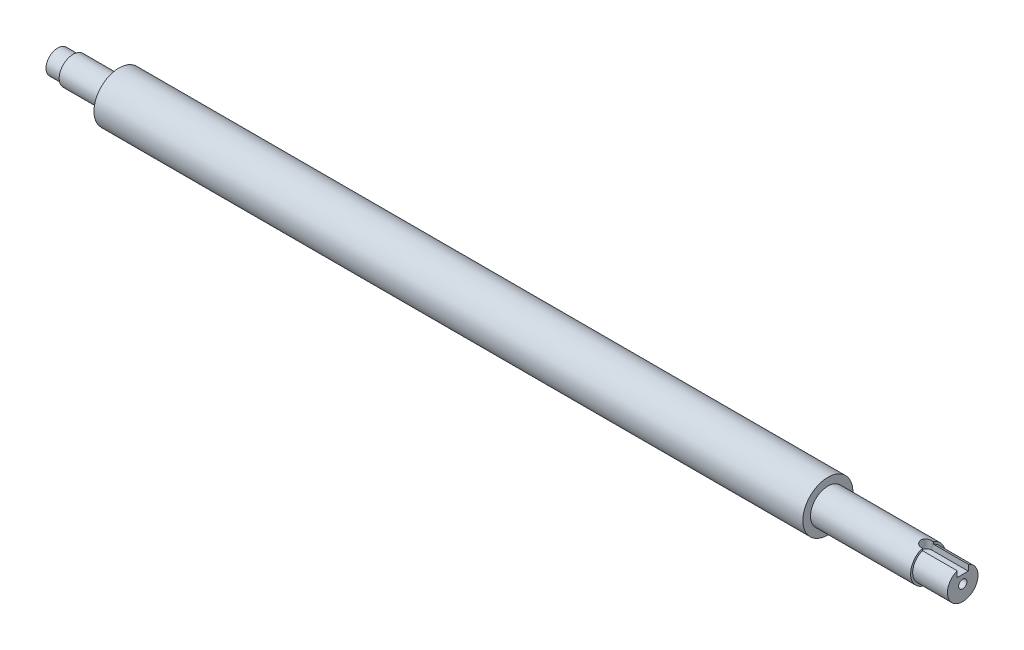
SolidWorks part; units mm, degrees
ref_plane "Front Plane" through (0, 0, 0) normal (0, 0, 1) x (1, 0, 0)
ref_plane "Top Plane" through (0, 0, 0) normal (0, 1, 0) x (1, 0, 0)
ref_plane "Right Plane" through (0, 0, 0) normal (1, 0, 0) x (0, 0, -1)
sketch "Sketch1" plane through (0, 0, 0) normal (0, 0, 1) x (1, 0, 0)
  line L0 (254.2407, 11) -> (279.2407, 11)
  line L1 (279.2407, 11) -> (279.2407, 0)
  line L2 (-360.7593, 8.5) -> (-371.7593, 8.5)
  line L3 (279.2407, 0) -> (-371.7593, 0)
  line L4 (-360.7593, 10) -> (-360.7593, 8.5)
  line L5 (182.2407, 18) -> (-327.7593, 18)
  line L6 (254.2407, 50.6061) -> (254.2407, -26.5676) construction
  line L7 (-327.7593, 10) -> (-360.7593, 10)
  line L8 (-361.2229, 15) -> (-361.2229, -3.8009) construction
  line L9 (-327.7593, 18) -> (-327.7593, 10)
  line L10 (-361.2229, 20) -> (-361.2229, -20) construction
  line L11 (-361.2229, 9.1) -> (-361.2229, -9.1) construction
  line L12 (-371.7593, 8.5) -> (-371.7593, 0)
  line L13 (-333.7229, -65.1183) -> (-333.7229, 170) construction
  line L14 (182.2407, 18) -> (182.2407, 12.5)
  line L17 (182.2407, 12.5) -> (254.2407, 12.5)
  line L18 (254.2407, 12.5) -> (254.2407, 11)
  point P10 (-44.4306, 234.5066)
  point P11 (-369.5152, 234.5066)
  point P14 (-44.4306, 232.0066)
  point P15 (-369.5152, 232.0066)
  dimension "D2" = 12.5
  dimension "D4" = 10
  dimension "D1" = 25
  dimension "D3" = 11
  dimension "D5" = 18
  dimension "D6" = 8.5
  dimension "D7" = 11
  dimension "D8" = 510
  dimension "D9" = 33
  dimension "D10" = 72
revolve "Revolve1" add sketch "Sketch1" angle 360 about L3
ref_plane "Plane1" through (0, 20, 0) normal (0, 1, 0) x (1, 0, 0)
sketch "Sketch3" plane through (0, 20, 0) normal (0, 1, 0) x (1, 0, 0)
  line L0 (279.2407, 0) -> (253.2177, 0) construction
  line L1 (279.2407, -11) -> (279.2407, 11) construction
  line L2 (279.2407, -4) -> (253.2177, -4)
  line L3 (279.2407, 4) -> (253.2177, 4)
  arc A0 (279.2407, -4) -> (279.2407, 4) centre (279.2407, 0) ccw
  arc A1 (253.2177, 4) -> (253.2177, -4) centre (253.2177, 0) ccw
  point P5 (266.2292, 0)
  dimension "D1" = 8
extrude "Cut-Extrude1" cut sketch "Sketch3" against normal blind 14
sketch "Sketch4" plane through (279.2407, 0, 0) normal (1, 0, 0) x (0, 0, -1)
  circle A0 centre (0, 0) radius 3
  dimension "D1" = 6
extrude "Cut-Extrude2" cut sketch "Sketch4" against normal blind 25
